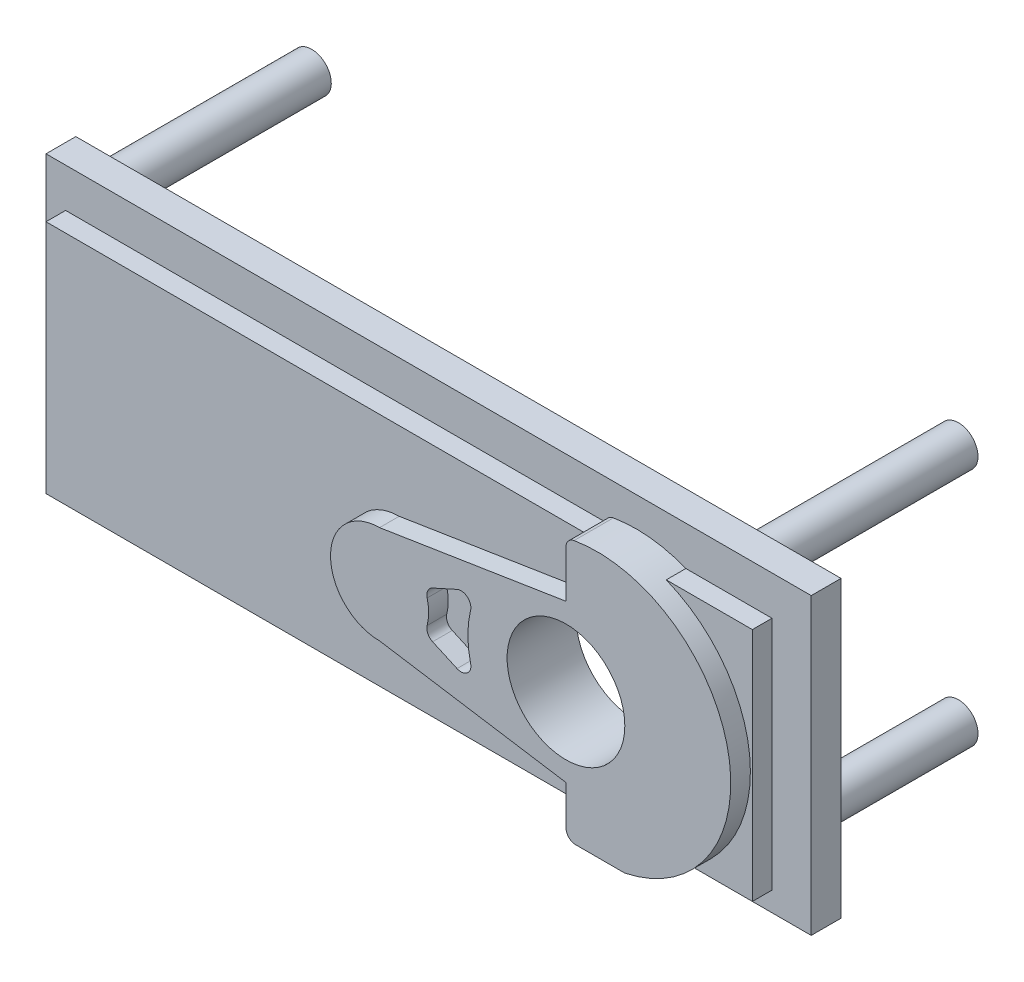
SolidWorks part; units mm, degrees
ref_plane "Piano frontale" through (0, 0, 0) normal (0, 0, 1) x (1, 0, 0)
ref_plane "Piano superiore" through (0, 0, 0) normal (0, 1, 0) x (1, 0, 0)
ref_plane "Piano destro" through (0, 0, 0) normal (1, 0, 0) x (0, 0, -1)
sketch "Schizzo1" plane through (0, 0, 0) normal (0, 0, 1) x (1, 0, 0)
  line L1 (-19.5, -7.5) -> (19.5, -7.5)
  line L2 (-19.5, -7.5) -> (-19.5, 7.5)
  line L3 (-19.5, 7.5) -> (19.5, 7.5)
  line L4 (19.5, -7.5) -> (19.5, 7.5)
  line L5 (-19.5, -7.5) -> (19.5, 7.5) construction
  line L6 (-19.5, 7.5) -> (19.5, -7.5) construction
  point P0 (0, 0)
  dimension "D1" = 39
  dimension "D2" = 15
extrude "Estrusione-Estrusione1" add sketch "Schizzo1" along normal blind 2.52
sketch "Schizzo2" plane through (0, 0, 2.52) normal (0, 0, 1) x (1, 0, 0)
  line L0 (-19.5, 7.5) -> (-19.5, -7.5) construction
  line L1 (-18.5, -6.5) -> (17.5, -6.5)
  line L2 (-18.5, -6.5) -> (-18.5, 5.5)
  line L3 (-18.5, 5.5) -> (17.5, 5.5)
  line L4 (17.5, -6.5) -> (17.5, 5.5)
  line L5 (-18.5, -6.5) -> (17.5, 5.5) construction
  line L6 (-18.5, 5.5) -> (17.5, -6.5) construction
  line L8 (19.5, -7.5) -> (19.5, 7.5) construction
  line L9 (19.5, 7.5) -> (-19.5, 7.5) construction
  line L10 (-19.5, -7.5) -> (19.5, -7.5) construction
  line L15 (19.5, -7.5) -> (19.5, 7.5)
  line L16 (19.5, 7.5) -> (-19.5, 7.5)
  line L17 (-19.5, 7.5) -> (-19.5, -7.5)
  line L18 (-19.5, -7.5) -> (19.5, -7.5)
  line L19 (19.5, -7.5) -> (19.5, 7.5)
  line L20 (19.5, 7.5) -> (-19.5, 7.5)
  line L21 (-19.5, 7.5) -> (-19.5, -7.5)
  line L22 (-19.5, -7.5) -> (19.5, -7.5)
  point P0 (0, 0)
  point P8 (0, 0)
  dimension "D1" = 1
  dimension "D2" = 2
  dimension "D3" = 2
  dimension "D4" = 1
  dimension "D5" = 0
extrude "Taglio-Estrusione1" cut sketch "Schizzo2" against normal blind 1
sketch "Schizzo3" plane through (0, 0, 2.52) normal (0, 0, 1) x (1, 0, 0)
  line L0 (19.5, -7.5) -> (19.5, 7.5) construction
  line L1 (-19.5, -7.5) -> (19.5, -7.5) construction
  circle A0 centre (9, -1) radius 3
  dimension "D1" = 6
  dimension "D2" = 10.5
  dimension "D3" = 6.5
extrude "Taglio-Estrusione2" cut sketch "Schizzo3" against normal up to next
sketch "Schizzo4" plane through (0, 0, 2.52) normal (0, 0, 1) x (1, 0, 0)
  line L0 (9, -1) -> (-3, -1) construction
  line L1 (-0.5, 1.5) -> (9, 3)
  line L2 (-0.5, -3.5) -> (9, -5)
  line L3 (9, 3) -> (9, 5.3928)
  line L4 (9, -5) -> (9, -7)
  line L5 (-19.5, -7.5) -> (19.5, -7.5) construction
  line L6 (9.5, -7.5) -> (12, -7.5)
  line L7 (17.5, 5.5) -> (-18.5, 5.5) construction
  line L8 (17.5, -6.5) -> (17.5, 5.5) construction
  line L9 (3.4482, 0.7469) -> (2.2043, 0.1862)
  line L10 (2.2043, -2.1862) -> (3.4482, -2.7469)
  arc A0 (-0.5, 1.5) -> (-0.5, -3.5) centre (-0.5, -1) ccw
  circle A1 centre (9, -1) radius 3 construction
  arc A3 (12, -7.5) -> (9.4143, 5.8854) centre (10.5824, -0.8314) ccw
  arc A4 (9.4143, 5.8854) -> (9, 5.3928) centre (9.5, 5.3928) ccw
  arc A5 (9.5, -7.5) -> (9, -7) centre (9.5, -7) cw
  arc A6 (2.2043, 0.1862) -> (1.9248, -0.3914) centre (2.4097, -0.2697) ccw
  arc A7 (1.9248, -1.6086) -> (1.9248, -0.3914) centre (-0.5, -1) ccw
  circle A8 centre (9, -1) radius 5
  arc A9 (4.1397, 0.1737) -> (4.1397, -2.1737) centre (9, -1) ccw
  arc A10 (1.9248, -1.6086) -> (2.2043, -2.1862) centre (2.4097, -1.7303) ccw
  arc A11 (4.1397, 0.1737) -> (3.4482, 0.7469) centre (3.6537, 0.2911) ccw
  arc A12 (3.4482, -2.7469) -> (4.1397, -2.1737) centre (3.6537, -2.2911) ccw
  circle A13 centre (9, -1) radius 3
  point P19 (17.4, -0.8314)
  point P27 (9, 5.8)
  point P30 (9, -7.5)
  point P33 (0, 0)
  point P34 (0, 0)
  point P37 (1.7913, 0)
  point P40 (1.7913, -2)
  point P43 (4.5263, 1.2329)
  point P46 (4.5263, -3.2329)
  dimension "D2" = 5
  dimension "D3" = 4
  dimension "D8" = 0.5
  dimension "D9" = 0.5
  dimension "D14" = 0.5
  dimension "D15" = 0.5
  dimension "D16" = 0.5
  dimension "D17" = 0.5
  dimension "D1" = 12
  dimension "D4" = 4
  dimension "D5" = 3
  dimension "D6" = 0.3
  dimension "D7" = 0.1
  dimension "D11" = 3
  dimension "D12" = 3
  dimension "D13" = 4.4657
  dimension "D10" = 2
extrude "Estrusione-Estrusione2" add sketch "Schizzo4" along normal blind 2 from surface at -1 starting at face at (-0.5, -0.5, 1.52)
sketch "Schizzo5" plane through (0, 0, 0) normal (0, 0, -1) x (-1, 0, 0)
  line L8 (-18.5, 6.5) -> (-18.5, -6.5)
  line L9 (-18.5, -6.5) -> (18.5, -6.5)
  line L10 (18.5, -6.5) -> (18.5, 6.5)
  line L11 (18.5, 6.5) -> (-18.5, 6.5)
  line L12 (-18.5, 6.5) -> (-18.5, -6.5)
  line L13 (-18.5, -6.5) -> (18.5, -6.5)
  line L14 (18.5, -6.5) -> (18.5, 6.5)
  line L15 (18.5, 6.5) -> (-18.5, 6.5)
  dimension "D1" = 1
extrude "Taglio-Estrusione4" cut sketch "Schizzo5" against normal blind 1
sketch "Schizzo6" plane through (0, 0, 0) normal (0, 0, -1) x (-1, 0, 0)
  line L0 (-9, 4.9161) -> (-9, 4.1539)
  line L4 (-9, -6.1539) -> (-9, -6.9161)
  arc A7 (-9.8095, 3.1722) -> (-9.8095, -5.1722) centre (-9, -1) ccw
  arc A8 (-10.1667, 5.9021) -> (-10.1667, -7.9021) centre (-9, -1) ccw
  arc A9 (-9, 4.9161) -> (-10.1667, 5.9021) centre (-10, 4.9161) ccw
  arc A10 (-9, 4.1539) -> (-9.8095, 3.1722) centre (-10, 4.1539) cw
  arc A11 (-9, -6.1539) -> (-9.8095, -5.1722) centre (-10, -6.1539) ccw
  arc A12 (-9, -6.9161) -> (-10.1667, -7.9021) centre (-10, -6.9161) cw
  point P8 (-9, 6)
  point P15 (-9, -8)
  dimension "D2" = 14
  dimension "D3" = 1
  dimension "D4" = 1
  dimension "D5" = 1
  dimension "D1" = 8.5
  dimension "D6" = 1
extrude "Taglio-Estrusione9" cut sketch "Schizzo6" against normal blind 1.5
sketch "Schizzo11" plane through (0, 0, 0) normal (0, 0, -1) x (-1, 0, 0)
  line L0 (19.5, -7.5) -> (-9.1882, -7.5) construction
  line L5 (19.5, 7.5) -> (19.5, -7.5) construction
  line L6 (-19.5, 7.5) -> (19.5, 7.5) construction
  line L13 (-19.5, -7.5) -> (-19.5, 7.5) construction
  line L14 (-11.5981, -7.5) -> (-19.5, -7.5) construction
  circle A0 centre (-15.48, -5.8644) radius 1
  circle A1 centre (-15.48, 6.3644) radius 1
  circle A2 centre (17.48, 6.3644) radius 1
  circle A3 centre (17.48, -5.8644) radius 1
  point P12 (0, 0)
  point P17 (19.5, -5.8171)
  point P18 (0, 0)
  point P19 (0, 0)
  point P22 (0, 0)
  point P25 (-19.5, 4.9078)
  point P26 (-19.5, 6.231)
  point P27 (0, 0)
  dimension "D1" = 2
  dimension "D2" = 1.6356
  dimension "D3" = 2.02
  dimension "D4" = 1.1356
  dimension "D5" = 2.02
  dimension "D6" = 1.1356
  dimension "D7" = 4.02
  dimension "D8" = 1.6356
  dimension "D9" = 4.02
extrude "Estrusione-Estrusione3" add sketch "Schizzo11" along normal blind 11 from surface at -1 starting at face at (7.1674, -0.4068, 1)
sketch "Schizzo12" plane through (0, 0, 1) normal (0, 0, -1) x (-1, 0, 0)
  line L2 (19.5, -7.5) -> (-9.1882, -7.5) construction
  line L3 (-19.5, -7.5) -> (-19.5, 7.5) construction
  circle A0 centre (-0.2, -2) radius 1
  dimension "D1" = 2
  dimension "D2" = 5.5
  dimension "D3" = 19.3
extrude "Taglio-Estrusione10" cut sketch "Schizzo12" against normal blind 1.5
sketch "Schizzo13" plane through (0, 0, 1) normal (0, 0, -1) x (-1, 0, 0)
  circle A0 centre (-9, -1) radius 3
  circle A1 centre (-9, -1) radius 4.25
  circle A2 centre (-9, -1) radius 3 construction
  arc A3 (-9.8095, 3.1722) -> (-9.8095, -5.1722) centre (-9, -1) ccw construction
extrude "Estrusione-Estrusione4" add sketch "Schizzo13" along normal blind 1
